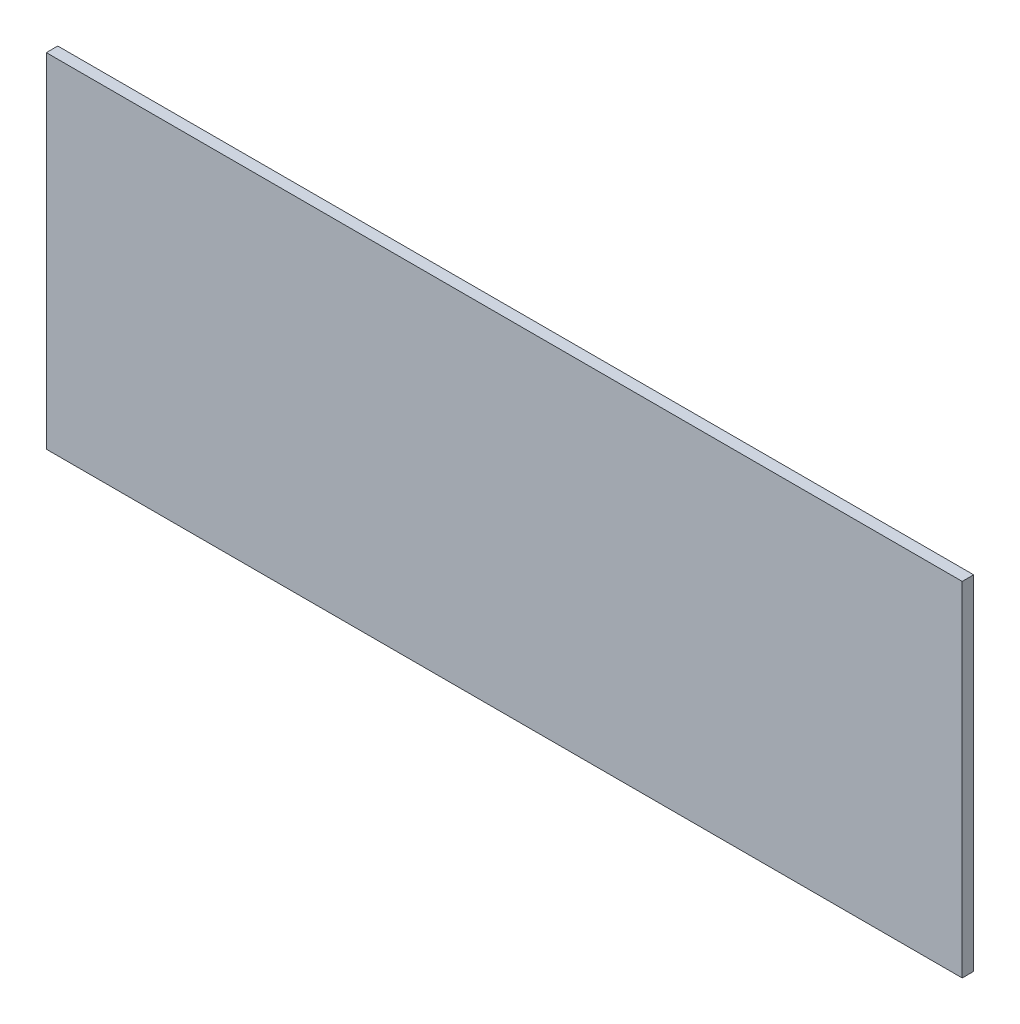
SolidWorks part; units mm, degrees
ref_plane "前基準面" through (0, 0, 0) normal (0, 0, 1) x (1, 0, 0)
ref_plane "上基準面" through (0, 0, 0) normal (0, 1, 0) x (1, 0, 0)
ref_plane "右基準面" through (0, 0, 0) normal (1, 0, 0) x (0, 0, -1)
sketch "草圖1" plane through (0, 0, 0) normal (0, 0, 1) x (1, 0, 0)
  line L1 (0, 0) -> (-80, 0)
  line L2 (0, 0) -> (0, 30)
  line L3 (0, 30) -> (-80, 30)
  line L4 (-80, 0) -> (-80, 30)
  dimension "D1" = 80
  dimension "D2" = 30
extrude "填料-伸長1" add sketch "草圖1" along normal blind 1
